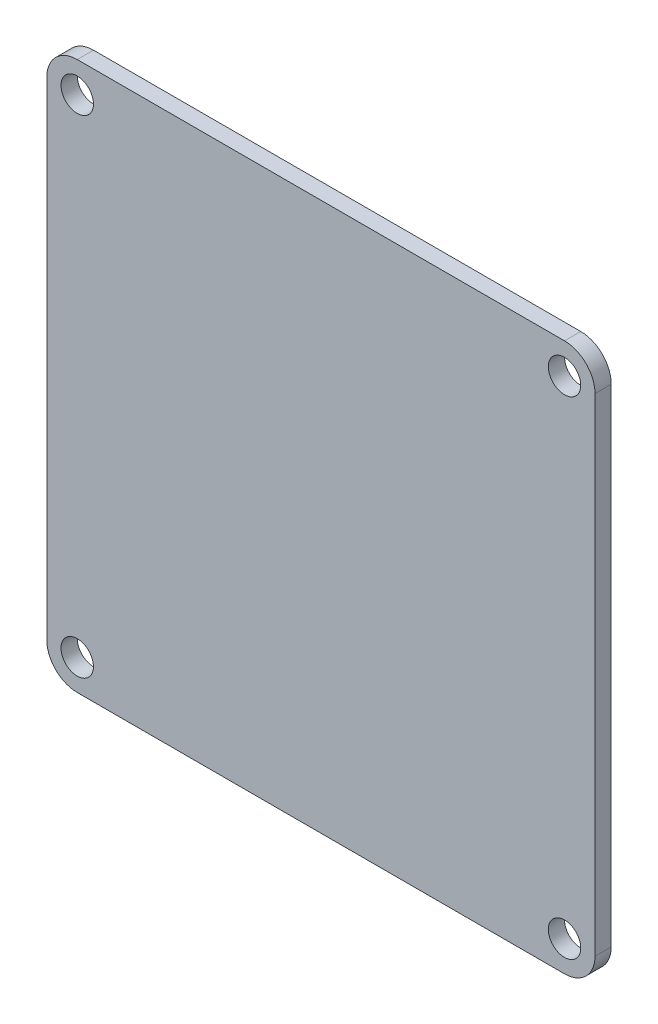
SolidWorks part; units mm, degrees
ref_plane "Front Plane" through (0, 0, 0) normal (0, 0, 1) x (1, 0, 0)
ref_plane "Top Plane" through (0, 0, 0) normal (0, 1, 0) x (1, 0, 0)
ref_plane "Right Plane" through (0, 0, 0) normal (1, 0, 0) x (0, 0, -1)
sketch "Sketch1" plane through (0, 0, 0) normal (0, 0, 1) x (1, 0, 0)
  line L0 (-38.4513, 0) -> (40.9958, 0) construction
  line L1 (-33.75, 33.75) -> (33.75, 33.75)
  line L2 (-33.75, 33.75) -> (-33.75, -33.75)
  line L3 (-33.75, -33.75) -> (33.75, -33.75)
  line L4 (33.75, 33.75) -> (33.75, -33.75)
  line L5 (-33.75, 33.75) -> (33.75, -33.75) construction
  line L6 (-33.75, -33.75) -> (33.75, 33.75) construction
  line L7 (-30, -30) -> (30, -30)
  line L8 (-30, -30) -> (-30, 30)
  line L9 (-30, 30) -> (30, 30)
  line L10 (30, -30) -> (30, 30)
  line L11 (-30, -30) -> (30, 30) construction
  line L12 (-30, 30) -> (30, -30) construction
  line L13 (0, 56.1358) -> (0, -50.321) construction
  arc A1 (-30, 33.75) -> (-33.75, 30) centre (-30, 30) ccw
  circle A2 centre (-30, 30) radius 0.1927
  circle A3 centre (-30, 30) radius 1.9974
  arc A4 (-30, -33.75) -> (-33.75, -30) centre (-30, -30) cw
  circle A5 centre (-30, -30) radius 1.9974
  arc A6 (30, -33.75) -> (33.75, -30) centre (30, -30) ccw
  circle A7 centre (30, -30) radius 1.9974
  arc A8 (30, 33.75) -> (33.75, 30) centre (30, 30) cw
  circle A9 centre (30, 30) radius 1.9974
  point P0 (0, 0)
  point P6 (0, 0)
  dimension "D3" = 3.9948
  dimension "D1" = 67.5
  dimension "D2" = 60
extrude "Boss-Extrude2" add sketch "Sketch1" along normal blind 2 contours L10 A9 L9 A3 L8 A5 L7 A7 | A8 L1 A1 L2 A4 L3 A6 L4 L9 A9 L10 A7 L7 A5 L8 A3
